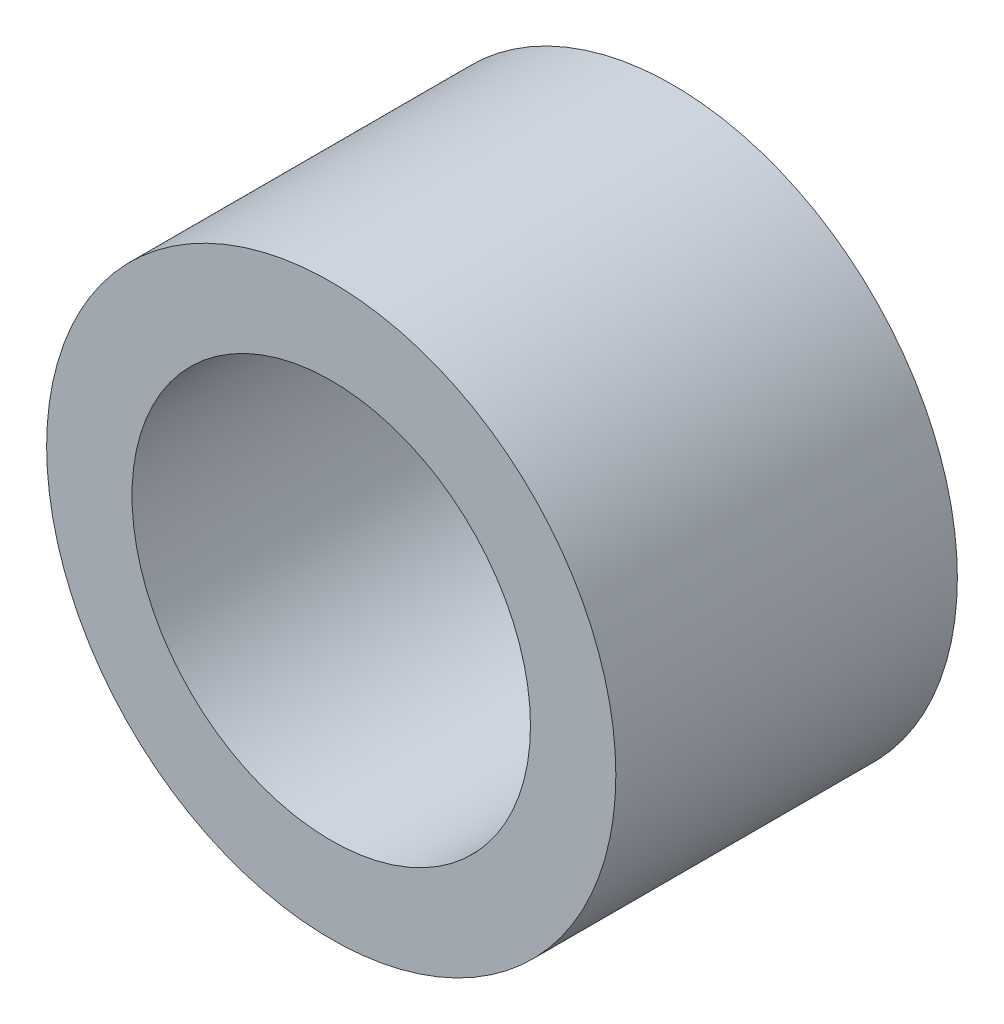
SolidWorks part; units mm, degrees
material "Q235A"
ref_plane "前视" through (0, 0, 0) normal (0, 0, 1) x (1, 0, 0)
ref_plane "上视" through (0, 0, 0) normal (0, 1, 0) x (1, 0, 0)
ref_plane "右视" through (0, 0, 0) normal (1, 0, 0) x (0, 0, -1)
sketch "草图1" plane through (0, 0, 0) normal (0, 0, 1) x (1, 0, 0)
  circle A0 centre (0, 0) radius 30
  circle A1 centre (0, 0) radius 21
  dimension "D1" = 42
  dimension "D2" = 60
extrude "凸台-拉伸1" add sketch "草图1" along normal mid plane 36
